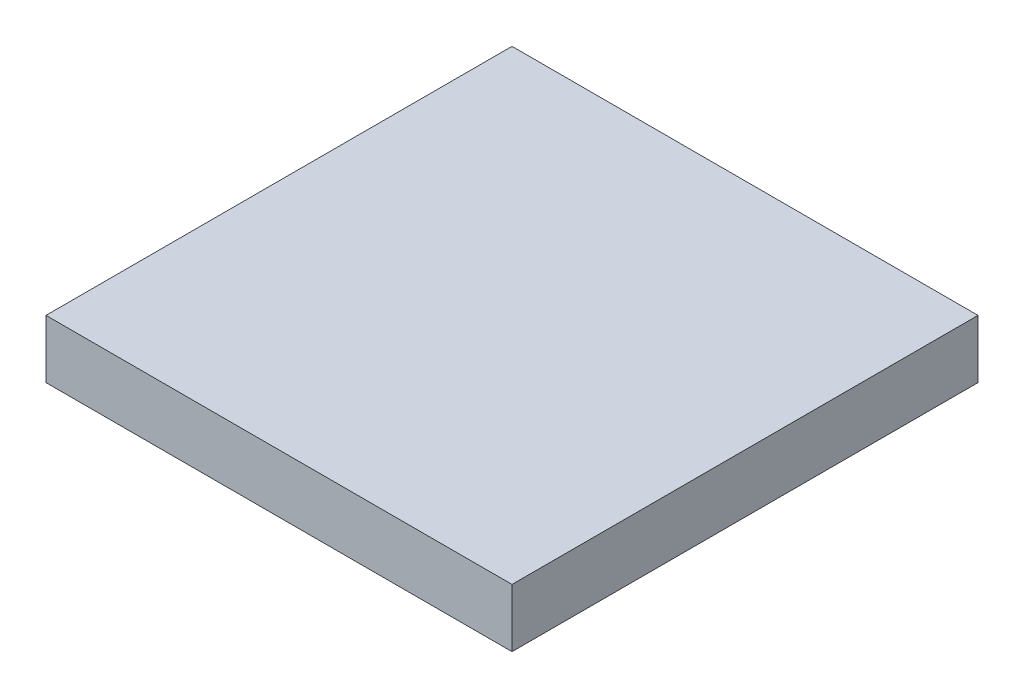
SolidWorks part; units mm, degrees
ref_plane "Front Plane" through (0, 0, 0) normal (0, 0, 1) x (1, 0, 0)
ref_plane "Top Plane" through (0, 0, 0) normal (0, 1, 0) x (1, 0, 0)
ref_plane "Right Plane" through (0, 0, 0) normal (1, 0, 0) x (0, 0, -1)
sketch "Sketch1" plane through (0, 0, 0) normal (0, 1, 0) x (1, 0, 0)
  line L1 (-1219.2, -1219.2) -> (1219.2, -1219.2)
  line L2 (-1219.2, -1219.2) -> (-1219.2, 1219.2)
  line L3 (-1219.2, 1219.2) -> (1219.2, 1219.2)
  line L4 (1219.2, -1219.2) -> (1219.2, 1219.2)
  line L5 (-1219.2, -1219.2) -> (1219.2, 1219.2) construction
  line L6 (-1219.2, 1219.2) -> (1219.2, -1219.2) construction
  point P0 (0, 0)
  dimension "D1" = 2438.4
  dimension "D2" = 2438.4
extrude "Boss-Extrude1" add sketch "Sketch1" along normal blind 304.8
sketch "Sketch2" [suppressed] plane through (0, 304.8, 0) normal (0, 1, 0) x (1, 0, 0)
  line L0 (0, 1219.2) -> (0, -1219.2) construction
  line L1 (1219.2, 1219.2) -> (-1219.2, 1219.2) construction
  line L2 (-1219.2, -1219.2) -> (1219.2, -1219.2) construction
  line L4 (-609.6, 609.6) -> (609.6, 609.6)
  line L5 (-609.6, 609.6) -> (-609.6, -1219.2)
  line L6 (-609.6, -1219.2) -> (609.6, -1219.2)
  line L7 (609.6, 609.6) -> (609.6, -1219.2)
  line L8 (-609.6, 609.6) -> (609.6, -1219.2) construction
  line L9 (-609.6, -1219.2) -> (609.6, 609.6) construction
  point P6 (0, -304.8)
  dimension "D1" = 1828.8
  dimension "D2" = 1219.2
extrude "Cut-Extrude1" [suppressed] cut sketch "Sketch2" against normal through all
